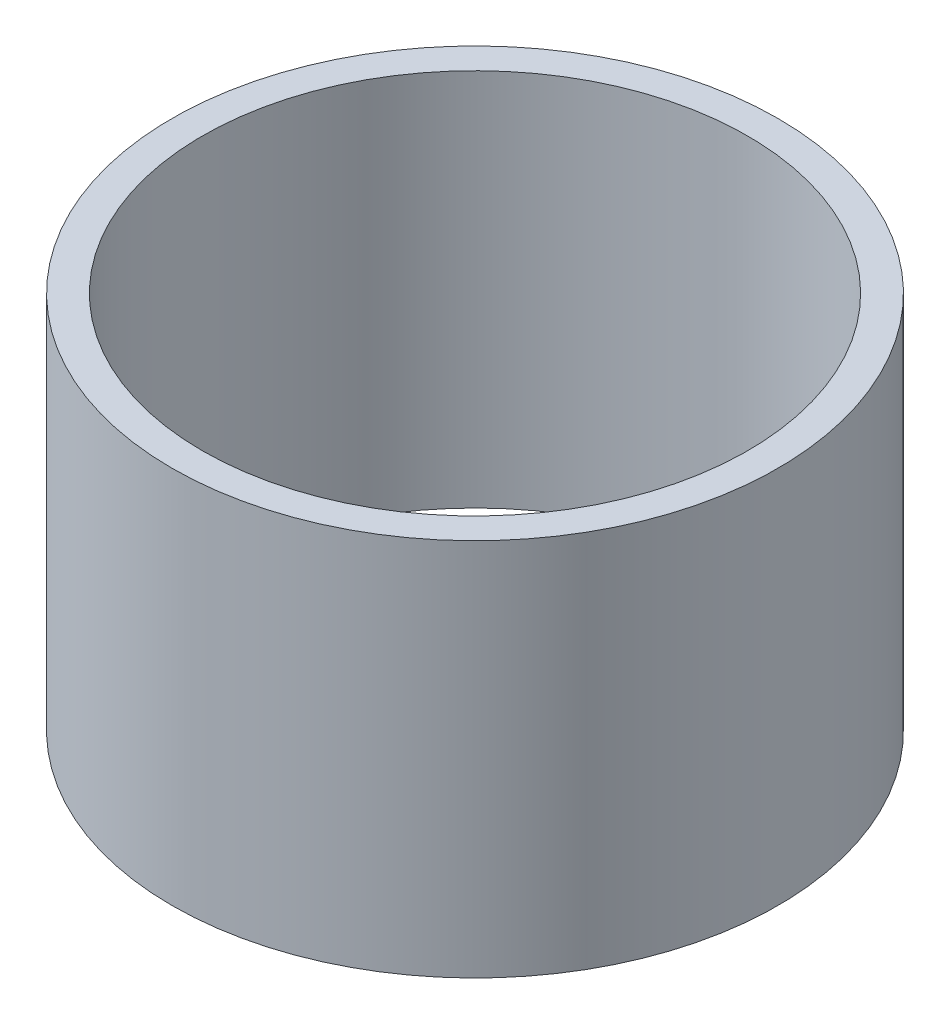
SolidWorks part; units mm, degrees
ref_plane "Front Plane" through (0, 0, 0) normal (0, 0, 1) x (1, 0, 0)
ref_plane "Top Plane" through (0, 0, 0) normal (0, 1, 0) x (1, 0, 0)
ref_plane "Right Plane" through (0, 0, 0) normal (1, 0, 0) x (0, 0, -1)
sketch "Sketch1" plane through (0, 0, 0) normal (0, 1, 0) x (1, 0, 0)
  circle A0 centre (0, 0) radius 36
  circle A1 centre (0, 0) radius 40
  dimension "D1" = 80
  dimension "D2" = 4
extrude "Boss-Extrude1" add sketch "Sketch1" along normal blind 50
